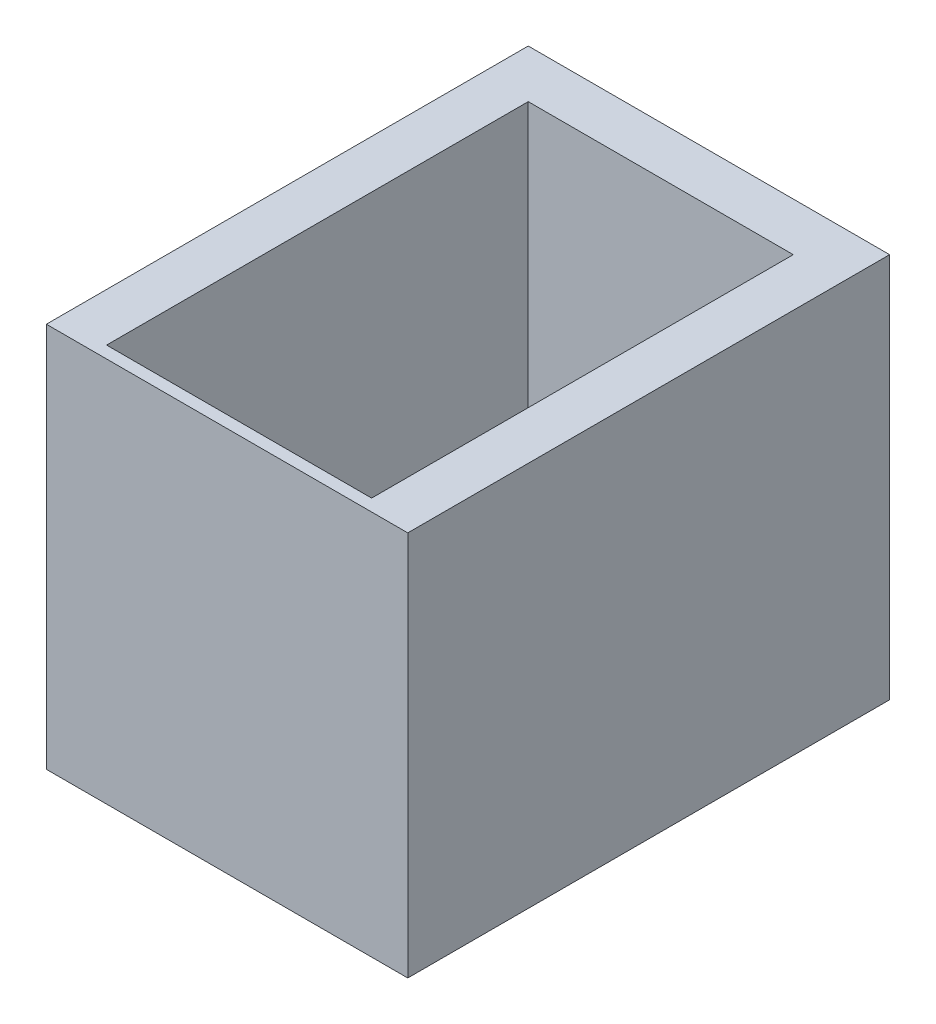
SolidWorks part; units mm, degrees
ref_plane "Front Plane" through (0, 0, 0) normal (0, 0, 1) x (1, 0, 0)
ref_plane "Top Plane" through (0, 0, 0) normal (0, 1, 0) x (1, 0, 0)
ref_plane "Right Plane" through (0, 0, 0) normal (1, 0, 0) x (0, 0, -1)
sketch "Sketch3" plane through (0, 0, 0) normal (0, 1, 0) x (1, 0, 0)
  line L1 (0, 0) -> (19.05, 0)
  line L2 (0, 0) -> (0, 25.4)
  line L3 (0, 25.4) -> (19.05, 25.4)
  line L4 (19.05, 0) -> (19.05, 25.4)
  dimension "D1" = 25.4
  dimension "D2" = 19.05
extrude "Boss-Extrude1" add sketch "Sketch3" along normal blind 20.32
sketch "Sketch4" plane through (0, 20.32, 0) normal (0, 1, 0) x (1, 0, 0)
  line L0 (19.05, 0) -> (19.05, 25.4) construction
  line L1 (2.54, 22.86) -> (16.51, 22.86)
  line L2 (2.54, 22.86) -> (2.54, 2.54)
  line L3 (2.54, 2.54) -> (16.51, 2.54)
  line L4 (16.51, 22.86) -> (16.51, 2.54)
  line L5 (19.05, 25.4) -> (0, 25.4) construction
  dimension "D1" = 20.32
  dimension "D2" = 13.97
  dimension "D3" = 2.54
  dimension "D4" = 2.54
extrude "Cut-Extrude1" cut sketch "Sketch4" against normal blind 17.78 contours L2 L3 L4 L1
sketch "Sketch6" plane through (0, 0, 0) normal (-1, 0, 0) x (0, 0, 1)
  line L3 (-25.4, 20.32) -> (0, 20.32) construction
  line L4 (-2.5627, 20.32) -> (-0.635, 20.32)
  line L6 (-2.5627, 12.679) -> (-2.5627, 20.32)
  line L7 (-2.5627, 12.679) -> (-0.635, 20.32)
  point P3 (0, 0)
  point P4 (0, 20.32)
  point P5 (0, 20.32)
  point P10 (-0.9653, 20.32)
  point P11 (-2.5627, 12.679)
  point P12 (0, 0)
  point P13 (0, 0)
  point P14 (0, 0)
  point P15 (0, 0)
  point P16 (0, 0)
  point P17 (0, 0)
  point P18 (0, 0)
extrude "Cut-Extrude3" cut sketch "Sketch6" against normal blind 13.97 from offset 2.54 contours L4 L7 L6 offset against normal yes
